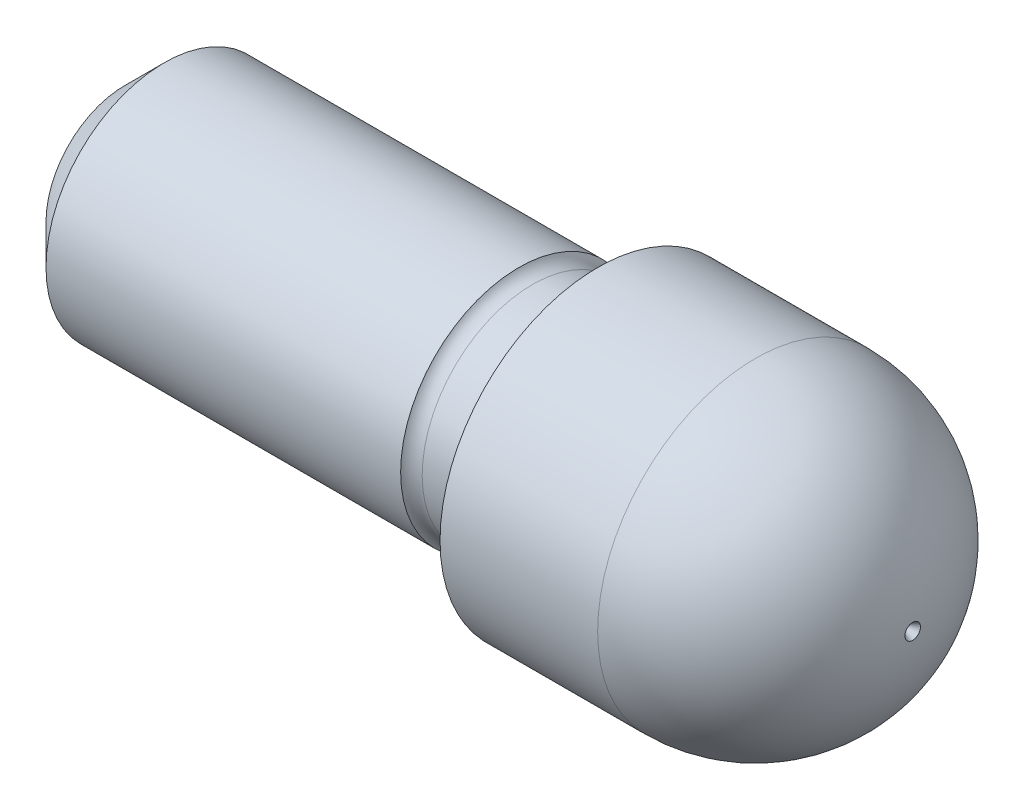
SolidWorks part; units mm, degrees
ref_plane "Front Plane" through (0, 0, 0) normal (0, 0, 1) x (1, 0, 0)
ref_plane "Top Plane" through (0, 0, 0) normal (0, 1, 0) x (1, 0, 0)
ref_plane "Right Plane" through (0, 0, 0) normal (1, 0, 0) x (0, 0, -1)
ref_plane "Plane1" through (0, 0, 0) normal (0, 0, -1) x (-1, 0, 0)
sketch "Sketch1" plane through (0, 0, 0) normal (0, 0, -1) x (-1, 0, 0)
  line L0 (-3.9976, 0.0986) -> (-3.8268, 0)
  line L1 (-3.8268, 0) -> (5.8268, 0)
  line L2 (5.8268, 0) -> (6, 0.1)
  line L3 (6, 0.1) -> (6, 1)
  line L4 (6, 1) -> (5.5, 1.5)
  line L5 (5.5, 1.5) -> (1, 1.5)
  line L6 (0.8268, 1.4) -> (0.2, 1.4)
  line L7 (0, 1.6) -> (0, 2)
  line L8 (0, 2) -> (-2, 2)
  line L9 (-4.0024, 0) -> (6, 0) construction
  arc A0 (1, 1.5) -> (0.8268, 1.4) centre (0.8268, 1.6) cw
  arc A1 (0.2, 1.4) -> (0, 1.6) centre (0.2, 1.6) cw
  arc A2 (-2, 2) -> (-3.9976, 0.0986) centre (-2, 0) ccw
revolve "Revolve1" add sketch "Sketch1" angle 360 about L9
